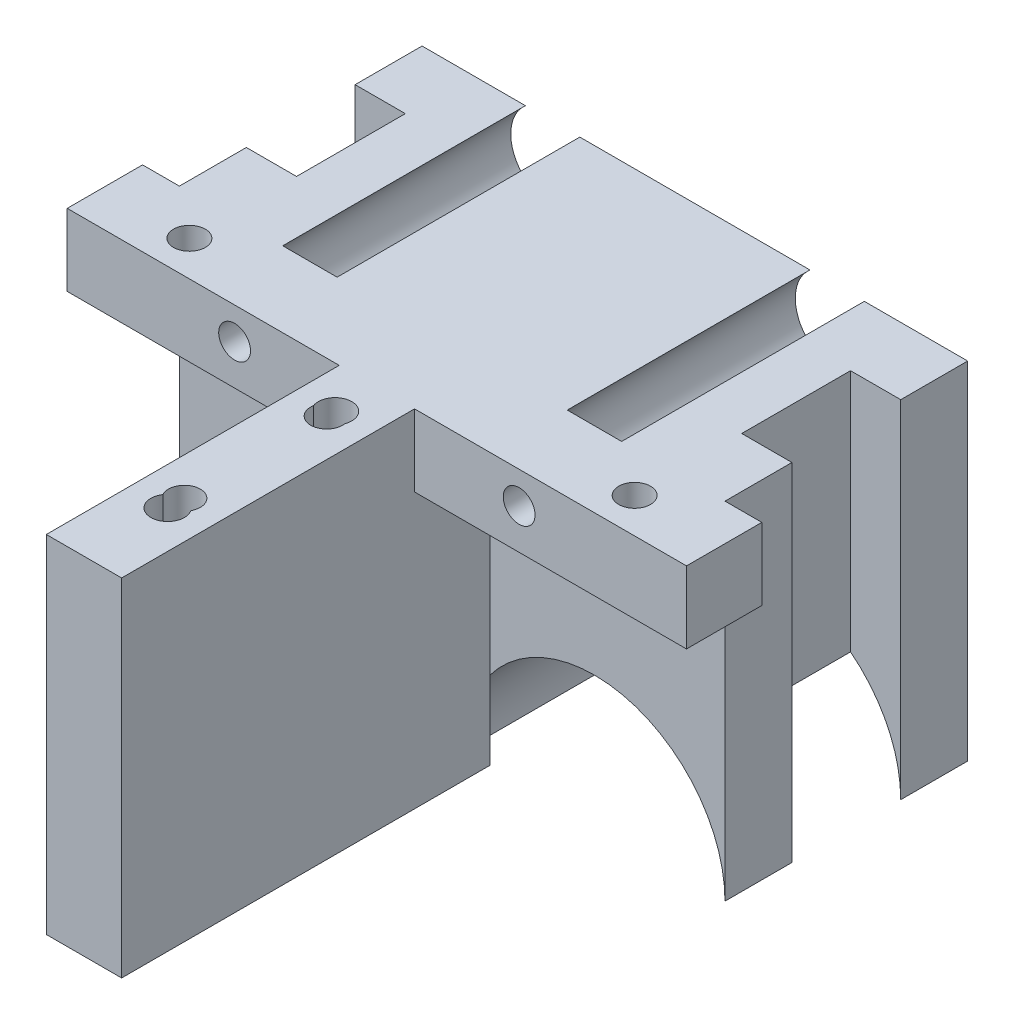
SolidWorks part; units mm, degrees
ref_plane "前视基准面" through (0, 0, 0) normal (0, 0, 1) x (1, 0, 0)
ref_plane "上视基准面" through (0, 0, 0) normal (0, 1, 0) x (1, 0, 0)
ref_plane "右视基准面" through (0, 0, 0) normal (1, 0, 0) x (0, 0, -1)
other "Configuration Table"
sketch "草图1" plane through (0, 0, 0) normal (0, 0, 1) x (1, 0, 0)
  line L0 (18.5882, -2.4) -> (-49981.4118, -2.4) construction
  line L1 (0, 0) -> (37, 0)
  line L2 (0, 0) -> (0, -4.8)
  line L3 (0, -4.8) -> (37, -4.8)
  line L4 (37, 0) -> (37, -4.8)
  circle A0 centre (10, -2.4) radius 0.95
  circle A1 centre (27, -2.4) radius 0.95
  point P9 (0, -2.4)
  dimension "D4" = 1.9
  dimension "D5" = 1.9
  dimension "D1" = 37
  dimension "D2" = 4.8
  dimension "D3" = 10
  dimension "D6" = 10
extrude "凸台-拉伸1" add sketch "草图1" along normal blind 4
sketch "草图4" plane through (0, 0, 0) normal (0, 1, 0) x (1, 0, 0)
  line L0 (2.2, 0) -> (2.2, 4)
  line L1 (37, 0) -> (0, 0) construction
  line L2 (2.2, 4) -> (5.2, 4)
  line L3 (5.2, 4) -> (5.2, 10.5)
  line L4 (5.2, 10.5) -> (2.2, 10.5)
  line L5 (2.2, 10.5) -> (2.2, 14.5)
  line L9 (2.2, 14.5) -> (34.8, 14.5)
  line L10 (0, -4) -> (0, 0) construction
  line L14 (34.8, 14.5) -> (34.8, 10.5)
  line L15 (34.8, 10.5) -> (31.8, 10.5)
  line L16 (31.8, 10.5) -> (31.8, 4)
  line L17 (31.8, 4) -> (34.8, 4)
  line L18 (34.8, 4) -> (34.8, 0)
  line L19 (37, -4) -> (37, 0) construction
  line L20 (34.8, 0) -> (2.2, 0)
  dimension "D1" = 2.2
  dimension "D2" = 4
  dimension "D3" = 6.5
  dimension "D4" = 4
  dimension "D5" = 3
  dimension "D8" = 4
  dimension "D9" = 6.5
  dimension "D10" = 4
  dimension "D11" = 3
  dimension "D12" = 2.2
extrude "凸台-拉伸2" add sketch "草图4" against normal blind 21.2
sketch "草图8" plane through (0, 0, 4) normal (0, 0, 1) x (1, 0, 0)
  line L0 (18.5, -4.8) -> (18.5, 49995.2) construction
  line L1 (0, -4.8) -> (37, -4.8) construction
  line L2 (38.4, -2.4) -> (-49961.6, -2.4) construction
  line L3 (37, -4.8) -> (37, 0) construction
  line L5 (16.25, 0) -> (20.75, 0)
  line L6 (16.25, 0) -> (16.25, -4.8)
  line L7 (16.25, -4.8) -> (20.75, -4.8)
  line L8 (20.75, 0) -> (20.75, -4.8)
  line L9 (16.25, 0) -> (20.75, -4.8) construction
  line L10 (16.25, -4.8) -> (20.75, 0) construction
  point P4 (18.5, -4.8)
  point P9 (37, -2.4)
  point P10 (18.5, -2.4)
  dimension "D1" = 4.5
extrude "凸台-拉伸4" add sketch "草图8" along normal blind 8
sketch "草图12" plane through (0, 0, 0) normal (0, 0, 1) x (1, 0, 0)
  line L0 (10, -2.4) -> (10, -50002.4) construction
  line L1 (27, -2.4) -> (27, -50002.4) construction
  line L2 (2.2, -21.2) -> (50002.2, -21.2) construction
  circle A0 centre (10, -21.2) radius 7.8
  circle A1 centre (27, -21.2) radius 7.8
extrude "切除-拉伸3" cut sketch "草图12" against normal blind 14.5
sketch "草图13" plane through (0, -4.8, 0) normal (0, -1, 0) x (1, 0, 0)
  line L0 (2.2, 0) -> (34.8, 0) construction
  line L1 (16.25, 0) -> (20.75, 0)
  line L2 (16.25, 0) -> (16.25, 22)
  line L3 (16.25, 22) -> (20.75, 22)
  line L4 (20.75, 0) -> (20.75, 22)
  line L5 (20.75, 12) -> (20.75, 4) construction
  line L6 (16.25, 12) -> (16.25, 4) construction
  line L7 (16.25, 12) -> (20.75, 12) construction
  dimension "D1" = 10
extrude "凸台-拉伸6" add sketch "草图13" along normal blind 16.4 and the other way blind 4.8
sketch "草图15" plane through (0, 0, 0) normal (0, 0, 1) x (1, 0, 0)
  circle A0 centre (10, -2.4) radius 2.5
  circle A1 centre (27, -2.4) radius 2.5
  dimension "D1" = 5
  dimension "D2" = 5
extrude "切除-拉伸4" cut sketch "草图15" against normal blind 14.5
sketch "草图16" plane through (0, 0, 4) normal (0, 0, 1) x (1, 0, 0)
  line L1 (0, 0) -> (37, 0)
  line L2 (0, 0) -> (0, -4.8)
  line L3 (0, -4.8) -> (37, -4.8)
  line L4 (37, 0) -> (37, -4.8)
  circle A0 centre (10, -2.4) radius 0.95
  circle A1 centre (27, -2.4) radius 0.95
  dimension "D1" = 1.9
  dimension "D2" = 1.9
extrude "凸台-拉伸8" add sketch "草图16" along normal blind 0.5
sketch "草图19" plane through (0, -21.2, 0) normal (0, -1, 0) x (1, 0, 0)
  line L0 (18.5, 22) -> (18.5, -49978) construction
  line L1 (20.75, 22) -> (16.25, 22) construction
  circle A0 centre (18.5, 7.5) radius 0.95
  circle A1 centre (18.5, 16) radius 0.95
  point P4 (18.5, 22)
  dimension "D2" = 1.9
  dimension "D4" = 1.9
  dimension "D1" = 14.5
  dimension "D3" = 6
extrude "切除-拉伸5" cut sketch "草图19" against normal blind 30
sketch "草图21" plane through (0, 0, -14.5) normal (0, 0, -1) x (-1, 0, 0)
  line L0 (0, 0) -> (0, -4.8) construction
  line L1 (-37, 0) -> (0, 0)
  line L2 (-37, 0) -> (-37, -0.5)
  line L3 (-37, -0.5) -> (0, -0.5)
  line L4 (0, 0) -> (0, -0.5)
  dimension "D1" = 0.5
extrude "切除-拉伸6" cut sketch "草图21" against normal through all
sketch "草图24" plane through (0, -0.5, 0) normal (0, 1, 0) x (1, 0, 0)
  line L0 (20.75, -22) -> (16.25, -22) construction
  circle A0 centre (18.5, -17) radius 1
  circle A1 centre (18.5, -7) radius 1
  dimension "D3" = 2
  dimension "D4" = 2
  dimension "D1" = 5
  dimension "D2" = 15
extrude "切除-拉伸7" cut sketch "草图24" against normal blind 30
sketch "草图25" plane through (0, -4.8, 0) normal (0, -1, 0) x (1, 0, 0)
  line L0 (2.2, -4) -> (5.2, -4) construction
  line L1 (31.8, -4) -> (34.8, -4) construction
  line L2 (5.2, -4) -> (5.2, -10.5) construction
  line L3 (31.8, -10.5) -> (31.8, -4) construction
  circle A0 centre (5.2, 2.4) radius 0.95
  circle A1 centre (31.8, 2.4) radius 0.95
  point P10 (0, 0)
  point P13 (0, 0)
  point P14 (0, 0)
  dimension "D2" = 1.9
  dimension "D4" = 1.9
  dimension "D1" = 6.4
  dimension "D3" = 6.4
extrude "切除-拉伸8" cut sketch "草图25" against normal blind 10
sketch "草图27" plane through (0, -4.8, 0) normal (0, -1, 0) x (-1, 0, 0)
  circle A0 centre (-5.2, -2.4) radius 2
  circle A1 centre (-31.8, -2.4) radius 2
  dimension "D1" = 4
  dimension "D2" = 4
extrude "切除-拉伸9" cut sketch "草图27" against normal blind 2
